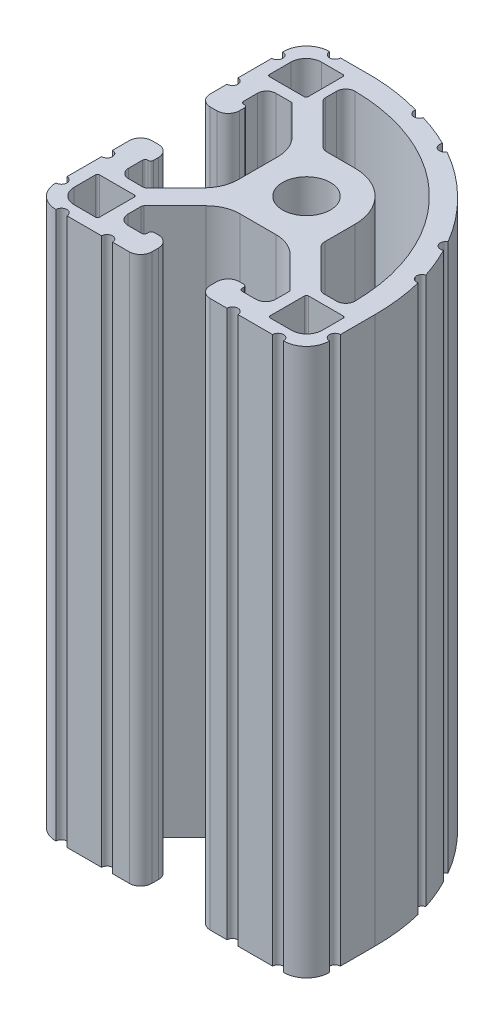
SolidWorks part; units mm, degrees
material "6061-T6 (SS)"
ref_plane "Front" through (0, 0, 0) normal (0, 0, 1) x (1, 0, 0)
ref_plane "Top" through (0, 0, 0) normal (0, 1, 0) x (1, 0, 0)
ref_plane "Right" through (0, 0, 0) normal (1, 0, 0) x (0, 0, -1)
sketch "Sketch1" plane through (0, 0, 0) normal (0, 0, 1) x (1, 0, 0)
  line L0 (0, -38.1) -> (0, 38.1)
  dimension "D1" = 76.2
other "15 1517 PROFILE(1)"
ref_plane "Plane1" through (0, -38.1, 0) normal (0, 1, 0) x (-1, 0, 0)
sketch "Sketch12" plane through (0, -38.1, 0) normal (0, 1, 0) x (-1, 0, 0)
  line L0 (0, 18.8774) -> (0, -24.5416) construction
  line L1 (24.2679, 0) -> (-24.0338, 0) construction
  line L3 (19.05, -19.05) -> (-19.05, -19.05) construction
  line L4 (11.8872, 16.9672) -> (11.8872, 12.0941)
  line L5 (12.1412, 11.8401) -> (17.018, 11.8401)
  line L6 (17.272, 12.0941) -> (17.272, 15.0876)
  line L7 (15.1384, 17.2212) -> (12.1412, 17.2212)
  line L8 (19.05, -19.05) -> (19.05, 19.05) construction
  line L9 (19.05, 19.05) -> (-19.05, 19.05) construction
  line L10 (-19.05, -19.05) -> (-19.05, 19.05) construction
  line L11 (19.05, -19.05) -> (-19.05, 19.05) construction
  line L12 (11.8923, -12.0941) -> (11.8923, -16.9672)
  line L13 (12.1463, -17.2212) -> (15.1384, -17.2212)
  line L14 (17.272, -15.0876) -> (17.272, -12.0941)
  line L15 (17.018, -11.8401) -> (12.1463, -11.8401)
  line L16 (19.05, 19.05) -> (-19.05, -19.05) construction
  line L22 (10.5713, -14.7676) -> (10.5713, -13.2314)
  line L23 (10.311, -12.6027) -> (4.8366, -7.1284)
  line L24 (3.9386, -6.7564) -> (0, -6.7564)
  line L25 (-6.7564, 0) -> (-6.7564, 4.2116)
  line L26 (-7.1284, 5.1096) -> (-12.3263, 10.3075)
  line L27 (-12.9549, 10.5679) -> (-14.7642, 10.5679)
  line L32 (-17.272, 15.0876) -> (-17.272, 12.1412)
  line L33 (-12.1412, 17.2212) -> (-15.1384, 17.2212)
  line L34 (-11.8872, 12.1412) -> (-11.8872, 16.9672)
  line L35 (-17.018, 11.8872) -> (-12.1412, 11.8872)
  line L78 (-5.8558, 8.1476) -> (-10.1754, 12.4672)
  line L79 (-10.287, 12.7366) -> (-10.287, 14.5699)
  line L80 (-8.8932, 15.9637) -> (-6.9992, 15.9637)
  line L81 (-6.6182, 15.5827) -> (-6.6182, 15.367)
  line L82 (-6.2372, 14.986) -> (-5.6388, 14.986)
  line L83 (-4.064, 16.5608) -> (-4.064, 17.4752)
  line L84 (-5.6388, 19.05) -> (-7.9758, 19.05)
  line L85 (-9.4998, 19.05) -> (-14.3282, 19.05)
  line L86 (-15.8522, 19.05) -> (-15.8759, 19.05)
  line L87 (-19.0509, 15.8761) -> (-19.0508, 15.8506)
  line L88 (-19.05, 14.3266) -> (-19.05, 12.7323)
  line L89 (-19.05, 12.7323) -> (-19.05, 9.525)
  line L90 (9.5111, -19.05) -> (12.7183, -19.05)
  line L91 (12.7183, -19.05) -> (14.3136, -19.05)
  line L92 (19.05, -14.2127) -> (19.05, -9.4945)
  line L93 (19.05, -7.9705) -> (19.05, -5.6388)
  line L94 (17.4752, -4.064) -> (16.5608, -4.064)
  line L95 (14.986, -5.6388) -> (14.986, -6.3233)
  line L96 (15.367, -6.7043) -> (15.4588, -6.7043)
  line L97 (15.8398, -7.0853) -> (15.8398, -9.017)
  line L98 (14.5698, -10.287) -> (12.4636, -10.287)
  line L99 (12.1942, -10.1754) -> (8.1486, -6.1298)
  line L100 (6.7564, -2.7688) -> (6.7564, 2.7688)
  line L101 (8.1486, 6.1298) -> (12.1942, 10.1754)
  line L102 (12.4636, 10.287) -> (14.5036, 10.287)
  line L103 (15.7736, 9.017) -> (15.7736, 7.0853)
  line L104 (15.3926, 6.7043) -> (15.367, 6.7043)
  line L105 (14.986, 6.3233) -> (14.986, 5.6388)
  line L106 (16.5608, 4.064) -> (17.4752, 4.064)
  line L107 (19.05, 5.6388) -> (19.05, 7.9759)
  line L108 (19.05, 9.4999) -> (19.05, 14.3284)
  line L109 (19.05, 15.8524) -> (19.05, 15.875)
  line L110 (15.875, 19.05) -> (15.847, 19.05)
  line L111 (14.323, 19.05) -> (9.4946, 19.05)
  line L112 (7.9706, 19.05) -> (5.6388, 19.05)
  line L113 (4.064, 17.4752) -> (4.064, 16.5608)
  line L114 (5.6388, 14.986) -> (6.2372, 14.986)
  line L115 (6.6182, 15.367) -> (6.6182, 15.5827)
  line L116 (6.9992, 15.9637) -> (8.8932, 15.9637)
  line L117 (10.287, 14.5699) -> (10.287, 12.7366)
  line L118 (10.1754, 12.4672) -> (5.8558, 8.1476)
  line L119 (2.4972, 6.7564) -> (-2.4972, 6.7564)
  arc A4 (12.1412, 17.2212) -> (11.8872, 16.9672) centre (12.1412, 16.9672) ccw
  arc A5 (11.8872, 12.0941) -> (12.1412, 11.8401) centre (12.1412, 12.0941) ccw
  arc A6 (17.018, 11.8401) -> (17.272, 12.0941) centre (17.018, 12.0941) ccw
  arc A7 (17.272, 15.0876) -> (15.1384, 17.2212) centre (15.1384, 15.0876) ccw
  arc A12 (11.8923, -16.9672) -> (12.1463, -17.2212) centre (12.1463, -16.9672) ccw
  arc A13 (15.1384, -17.2212) -> (17.272, -15.0876) centre (15.1384, -15.0876) ccw
  arc A14 (17.272, -12.0941) -> (17.018, -11.8401) centre (17.018, -12.0941) ccw
  arc A15 (12.1463, -11.8401) -> (11.8923, -12.0941) centre (12.1463, -12.0941) ccw
  arc A25 (9.269, -16.0372) -> (10.5713, -14.7676) centre (9.3013, -14.7676) ccw
  arc A26 (10.5713, -13.2314) -> (10.311, -12.6027) centre (9.6823, -13.2314) ccw
  arc A27 (4.8366, -7.1284) -> (3.9386, -6.7564) centre (3.9386, -8.0264) ccw
  arc A28 (-6.7564, 0) -> (0, -6.7564) centre (0, 0) ccw
  arc A29 (-6.7564, 4.2116) -> (-7.1284, 5.1096) centre (-8.0264, 4.2116) ccw
  arc A30 (-12.3263, 10.3075) -> (-12.9549, 10.5679) centre (-12.9549, 9.6789) ccw
  arc A31 (-14.7642, 10.5679) -> (-16.0341, 9.2879) centre (-14.7642, 9.2979) ccw
  arc A32 (-16.0341, 9.2879) -> (9.269, -16.0372) centre (9.4921, 9.4888) ccw
  circle A35 centre (0, 0) radius 3.3274
  arc A40 (-17.272, 12.1412) -> (-17.018, 11.8872) centre (-17.018, 12.1412) ccw
  arc A41 (-15.1384, 17.2212) -> (-17.272, 15.0876) centre (-15.1384, 15.0876) ccw
  arc A42 (-11.8872, 16.9672) -> (-12.1412, 17.2212) centre (-12.1412, 16.9672) ccw
  arc A43 (-12.1412, 11.8872) -> (-11.8872, 12.1412) centre (-12.1412, 12.1412) ccw
  arc A95 (-10.287, 12.7366) -> (-10.1754, 12.4672) centre (-9.906, 12.7366) ccw
  arc A96 (-8.8932, 15.9637) -> (-10.287, 14.5699) centre (-8.8932, 14.5699) ccw
  arc A97 (-6.6182, 15.5827) -> (-6.9992, 15.9637) centre (-6.9992, 15.5827) ccw
  arc A98 (-6.6182, 15.367) -> (-6.2372, 14.986) centre (-6.2372, 15.367) ccw
  arc A99 (-5.6388, 14.986) -> (-4.064, 16.5608) centre (-5.6388, 16.5608) ccw
  arc A100 (-4.064, 17.4752) -> (-5.6388, 19.05) centre (-5.6388, 17.4752) ccw
  arc A101 (-9.4998, 19.05) -> (-7.9758, 19.05) centre (-8.7378, 19.05) ccw
  arc A102 (-15.8522, 19.05) -> (-14.3282, 19.05) centre (-15.0902, 19.05) ccw
  arc A103 (-15.8759, 19.05) -> (-19.0509, 15.8761) centre (-15.8759, 15.875) ccw
  arc A104 (-19.05, 14.3266) -> (-19.0508, 15.8506) centre (-19.0504, 15.0886) ccw
  arc A105 (-19.05, 9.525) -> (-18.2241, 2.6723) centre (9.4921, 9.4888) ccw
  arc A106 (-17.8208, 1.2027) -> (-18.2241, 2.6723) centre (-18.0323, 1.9348) ccw
  arc A107 (-17.8208, 1.2027) -> (-16.0569, -3.0251) centre (9.3479, 10.0565) ccw
  arc A108 (-15.3417, -4.3707) -> (-16.0569, -3.0251) centre (-15.7082, -3.7026) ccw
  arc A109 (-15.3417, -4.3707) -> (-10.5738, -10.4703) centre (9.348, 10.0152) ccw
  arc A110 (-10.5738, -10.4703) -> (-4.4477, -15.1275) centre (9.6252, 9.7419) ccw
  arc A111 (-3.1021, -15.8427) -> (-4.4477, -15.1275) centre (-3.7797, -15.4941) ccw
  arc A112 (-3.1021, -15.8427) -> (1.3376, -17.6058) centre (9.6276, 9.7402) ccw
  arc A113 (2.8072, -18.0091) -> (1.3376, -17.6058) centre (2.0697, -17.8173) ccw
  arc A114 (2.8072, -18.0091) -> (9.5111, -19.05) centre (10.5124, 9.5075) ccw
  arc A115 (15.8376, -19.0507) -> (14.3136, -19.05) centre (15.0756, -19.0504) ccw
  arc A116 (15.8376, -19.0507) -> (19.05, -15.7367) centre (15.8781, -15.876) ccw
  arc A117 (19.05, -14.2127) -> (19.05, -15.7367) centre (19.05, -14.9747) ccw
  arc A118 (19.05, -7.9705) -> (19.05, -9.4945) centre (19.05, -8.7325) ccw
  arc A119 (19.05, -5.6388) -> (17.4752, -4.064) centre (17.4752, -5.6388) ccw
  arc A120 (16.5608, -4.064) -> (14.986, -5.6388) centre (16.5608, -5.6388) ccw
  arc A121 (14.986, -6.3233) -> (15.367, -6.7043) centre (15.367, -6.3233) ccw
  arc A122 (15.8398, -7.0853) -> (15.4588, -6.7043) centre (15.4588, -7.0853) ccw
  arc A123 (14.5698, -10.287) -> (15.8398, -9.017) centre (14.5698, -9.017) ccw
  arc A124 (12.1942, -10.1754) -> (12.4636, -10.287) centre (12.4636, -9.906) ccw
  arc A125 (6.7564, -2.7688) -> (8.1486, -6.1298) centre (11.5096, -2.7688) ccw
  arc A126 (8.1486, 6.1298) -> (6.7564, 2.7688) centre (11.5096, 2.7688) ccw
  arc A127 (12.4636, 10.287) -> (12.1942, 10.1754) centre (12.4636, 9.906) ccw
  arc A128 (15.7736, 9.017) -> (14.5036, 10.287) centre (14.5036, 9.017) ccw
  arc A129 (15.3926, 6.7043) -> (15.7736, 7.0853) centre (15.3926, 7.0853) ccw
  arc A130 (15.367, 6.7043) -> (14.986, 6.3233) centre (15.367, 6.3233) ccw
  arc A131 (14.986, 5.6388) -> (16.5608, 4.064) centre (16.5608, 5.6388) ccw
  arc A132 (17.4752, 4.064) -> (19.05, 5.6388) centre (17.4752, 5.6388) ccw
  arc A133 (19.05, 9.4999) -> (19.05, 7.9759) centre (19.05, 8.7379) ccw
  arc A134 (19.05, 15.8524) -> (19.05, 14.3284) centre (19.05, 15.0904) ccw
  arc A135 (19.05, 15.875) -> (15.875, 19.05) centre (15.875, 15.875) ccw
  arc A136 (14.323, 19.05) -> (15.847, 19.05) centre (15.085, 19.05) ccw
  arc A137 (7.9706, 19.05) -> (9.4946, 19.05) centre (8.7326, 19.05) ccw
  arc A138 (5.6388, 19.05) -> (4.064, 17.4752) centre (5.6388, 17.4752) ccw
  arc A139 (4.064, 16.5608) -> (5.6388, 14.986) centre (5.6388, 16.5608) ccw
  arc A140 (6.2372, 14.986) -> (6.6182, 15.367) centre (6.2372, 15.367) ccw
  arc A141 (6.9992, 15.9637) -> (6.6182, 15.5827) centre (6.9992, 15.5827) ccw
  arc A142 (10.287, 14.5699) -> (8.8932, 15.9637) centre (8.8932, 14.5699) ccw
  arc A143 (10.1754, 12.4672) -> (10.287, 12.7366) centre (9.906, 12.7366) ccw
  arc A144 (2.4972, 6.7564) -> (5.8558, 8.1476) centre (2.4972, 11.5062) ccw
  arc A145 (-5.8558, 8.1476) -> (-2.4972, 6.7564) centre (-2.4972, 11.5062) ccw
  point P76 (0, 19.05)
  point P207 (0, -19.05)
  point P208 (-19.05, 19.05)
  point P209 (19.05, -19.05)
  point P210 (0, 0)
  point P211 (-19.05, 0)
  point P212 (19.05, 0)
  point P213 (-19.05, -19.05)
  point P214 (19.05, 19.05)
  point P215 (0, 0)
  dimension "D1" = 6.6548
  dimension "D2" = 8.128
  dimension "D3" = 38.1
  dimension "D9" = 28.575
  dimension "D4" = 19.05
  dimension "D5" = 12.2936
  dimension "D6" = 4.064
  dimension "D7" = 20.574
  dimension "D8" = 3.9624
  dimension "D10" = 3.048
  dimension "D11" = 1.6002
  dimension "D12" = 5.3848
  dimension "D13" = 1.8288
